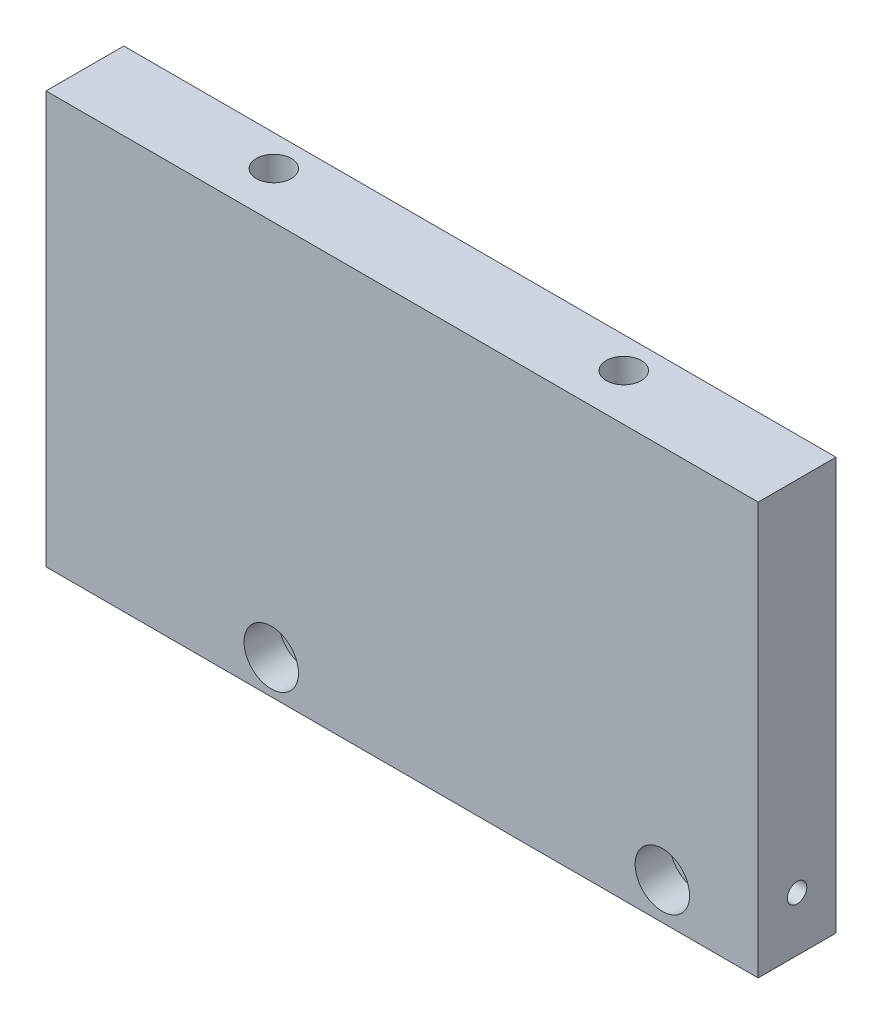
SolidWorks part; units mm, degrees
ref_plane "Front Plane" through (0, 0, 0) normal (0, 0, 1) x (1, 0, 0)
ref_plane "Top Plane" through (0, 0, 0) normal (0, 1, 0) x (1, 0, 0)
ref_plane "Right Plane" through (0, 0, 0) normal (1, 0, 0) x (0, 0, -1)
sketch "Sketch1" plane through (0, 0, 0) normal (0, 1, 0) x (1, 0, 0)
  line L1 (-45.79, 5) -> (45.79, 5)
  line L2 (-45.79, 5) -> (-45.79, -5)
  line L3 (-45.79, -5) -> (45.79, -5)
  line L4 (45.79, 5) -> (45.79, -5)
  line L5 (-45.79, 5) -> (45.79, -5) construction
  line L6 (-45.79, -5) -> (45.79, 5) construction
  point P0 (0, 0)
  dimension "D1" = 91.58
  dimension "D2" = 10
extrude "Boss-Extrude1" add sketch "Sketch1" along normal blind 53
sketch "Sketch2" plane through (0, 0, 5) normal (0, 0, 1) x (1, 0, 0)
  line L1 (-45.79, 0) -> (45.79, 0) construction
  line L2 (45.79, 53) -> (45.79, 0) construction
  circle A0 centre (33.464, 4.763) radius 1.75
  circle A1 centre (-16.828, 4.382) radius 1.75
  dimension "D2" = 3.5
  dimension "D3" = 4.382
  dimension "D5" = 4.763
  dimension "D1" = 62.618
  dimension "D4" = 12.326
extrude "Cut-Extrude1" cut sketch "Sketch2" against normal through all
sketch "Sketch4" plane through (0, 0, -5) normal (0, 0, -1) x (-1, 0, 0)
  line L0 (-45.79, 53) -> (45.79, 53) construction
  line L1 (30, 23) -> (15, 23)
  line L2 (30, 23) -> (30, 48)
  line L3 (30, 48) -> (15, 48)
  line L4 (15, 23) -> (15, 48)
  line L5 (-15, 48) -> (-30, 48)
  line L6 (-15, 48) -> (-15, 23)
  line L7 (-15, 23) -> (-30, 23)
  line L8 (-30, 48) -> (-30, 23)
  line L9 (-45.79, 53) -> (-45.79, 0) construction
  point P10 (22.5, 48)
  point P11 (-22.5, 48)
  dimension "D1" = 5
  dimension "D2" = 23.29
  dimension "D3" = 45
  dimension "D4" = 15
  dimension "D5" = 25
extrude "Cut-Extrude3" cut sketch "Sketch4" against normal blind 8
sketch "Sketch5" plane through (0, 53, 0) normal (0, 1, 0) x (1, 0, 0)
  line L0 (22.5, 1) -> (45.79, 1) construction
  line L2 (45.79, 5) -> (-45.79, 5) construction
  line L3 (45.79, -5) -> (45.79, 5) construction
  circle A0 centre (22.5, 1) radius 2.25
  circle A1 centre (-22.5, 1) radius 2.25
  dimension "D1" = 4.5
  dimension "D3" = 45
  dimension "D2" = 23.29
  dimension "D4" = 4
extrude "Cut-Extrude4" cut sketch "Sketch5" against normal blind 17
sketch "Sketch7" plane through (0, 0, 5) normal (0, 0, 1) x (1, 0, 0)
  circle A0 centre (33.464, 4.763) radius 3.5
  circle A1 centre (-16.828, 4.382) radius 3.5
  dimension "D1" = 7
extrude "Cut-Extrude5" cut sketch "Sketch7" against normal blind 4.5
sketch "Sketch10" plane through (-45.79, 0, 0) normal (-1, 0, 0) x (0, 0, 1)
  line L0 (-5, 0) -> (5, 0) construction
  point P0 (0, 7)
  dimension "D1" = 7
hole_wizard "M3 Tapped Hole1" positions "Sketch10" profile "Sketch9" tap size "M3" standard "ISO"
sketch "Sketch9" plane through (-45.79, 7, 0) normal (0, 1, 0) x (0, 0, 1)
  line L0 (0, 0) -> (0, 8.2511)
  line L1 (0, 8.2511) -> (1.25, 7.5)
  line L2 (1.25, 7.5) -> (1.25, 0)
  line L5 (1.25, 0) -> (0, 0)
  line L10 (0, 8.2511) -> (-1.25, 7.5) construction
  line L11 (0, -6.35) -> (0, 107.95) construction
  dimension "Tap Drill Dia." = 2.5
  dimension "Tap Drill Depth" = 7.5
  dimension "Drill Angle" = 118
cosmetic thread "Hole Thread1" parameters "D1"=6, "D2"=3
mirror "Mirror1" about plane through (0, 0, 0) normal (1, 0, 0) of "M3 Tapped Hole1"
cosmetic thread "Hole Thread2" parameters "D1"=6, "D2"=3
fillet "Fillet1" radius 2.5 8 edges at (-30, 48, -1) (-15, 23, -1) (-30, 23, -1) (-15, 48, -1) (30, 48, -1) (30, 23, -1) (15, 23, -1) (15, 48, -1)
